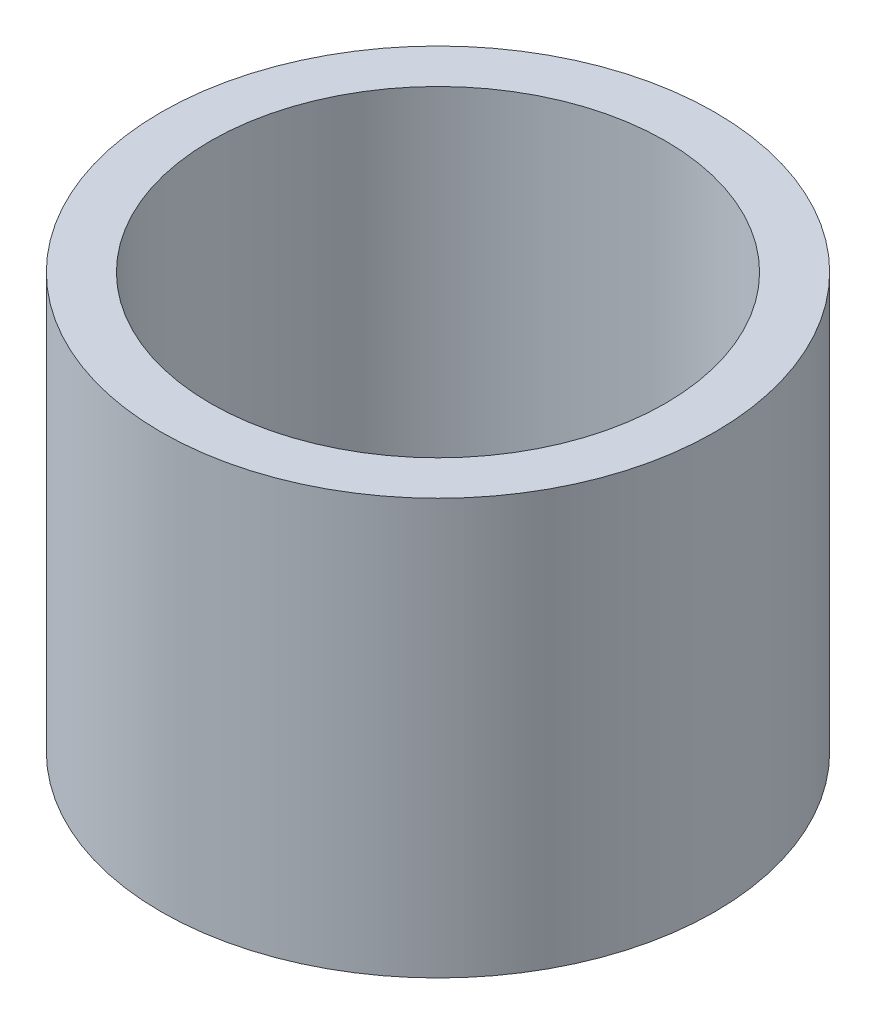
SolidWorks part; units mm, degrees
material "Leaded Commercial Bronze"
ref_plane "Front Plane" through (0, 0, 0) normal (0, 0, 1) x (1, 0, 0)
ref_plane "Top Plane" through (0, 0, 0) normal (0, 1, 0) x (1, 0, 0)
ref_plane "Right Plane" through (0, 0, 0) normal (1, 0, 0) x (0, 0, -1)
sketch "Sketch1" plane through (0, 0, 0) normal (0, 1, 0) x (1, 0, 0)
  circle A0 centre (0, 0) radius 10.4275
  circle A1 centre (0, 0) radius 12.7
  dimension "D1" = 20.855
extrude "Boss-Extrude1" add sketch "Sketch1" along normal blind 19.05
